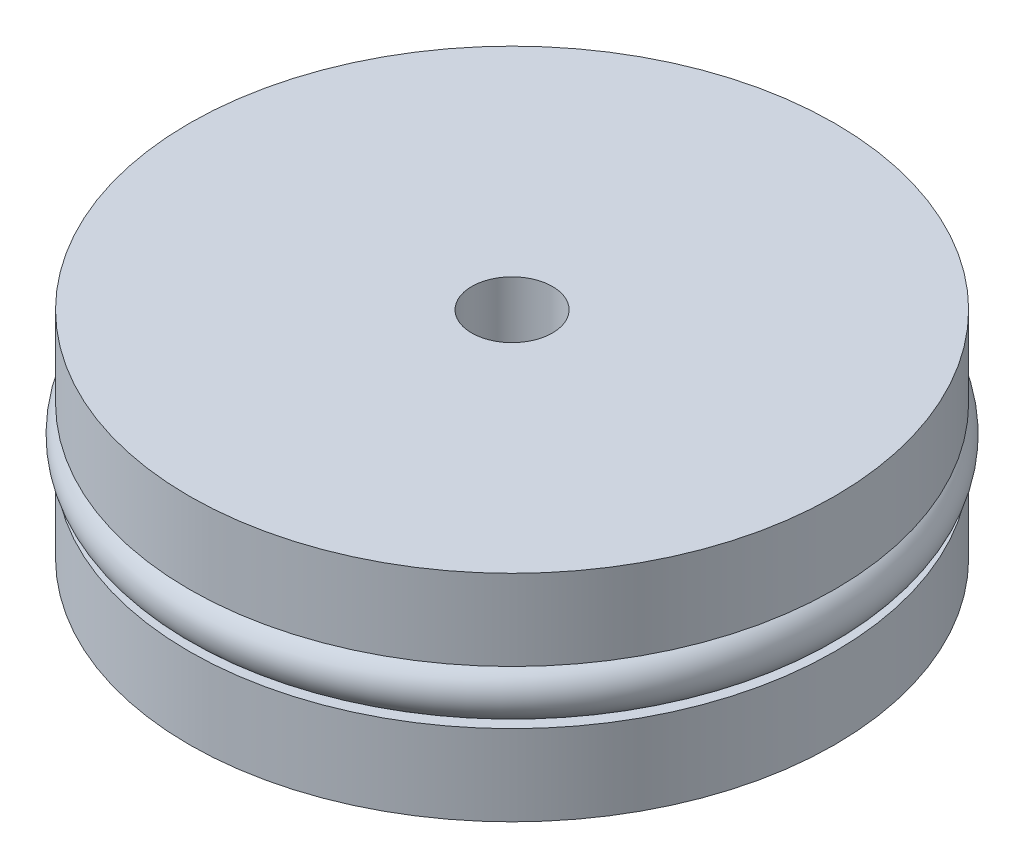
SolidWorks part; units mm, degrees
ref_plane "Front Plane" through (0, 0, 0) normal (0, 0, 1) x (1, 0, 0)
ref_plane "Top Plane" through (0, 0, 0) normal (0, 1, 0) x (1, 0, 0)
ref_plane "Right Plane" through (0, 0, 0) normal (1, 0, 0) x (0, 0, -1)
sketch "Sketch1" plane through (0, 0, 0) normal (0, 1, 0) x (1, 0, 0)
  circle A0 centre (0, 0) radius 12
  dimension "D1" = 24
extrude "Boss-Extrude1" add sketch "Sketch1" along normal mid plane 8
sketch "Sketch2" plane through (0, 0, 0) normal (0, 1, 0) x (1, 0, 0)
  circle A0 centre (0, 0) radius 10.25
  circle A1 centre (0, 0) radius 12 construction
  circle A2 centre (0, 0) radius 12
  dimension "D1" = 20.5
extrude "Cut-Extrude1" cut sketch "Sketch2" against normal mid plane 2
sketch "Sketch3" plane through (0, 0, 0) normal (0, 0, 1) x (1, 0, 0)
  line L0 (0, 4) -> (0, -4) construction
  line L1 (12, 4) -> (-12, 4) construction
  line L2 (-12, -4) -> (12, -4) construction
  line L3 (-10.25, 1) -> (-10.25, -1) construction
  circle A0 centre (-11.25, 0) radius 1
  point P6 (0, 0)
  dimension "D1" = 2
revolve "Revolve1" add sketch "Sketch3" angle 360 about L0
sketch "Sketch4" plane through (0, 4, 0) normal (0, 1, 0) x (1, 0, 0)
  circle A0 centre (0, 0) radius 1.5
  dimension "D1" = 3
extrude "Cut-Extrude2" cut sketch "Sketch4" against normal through all
